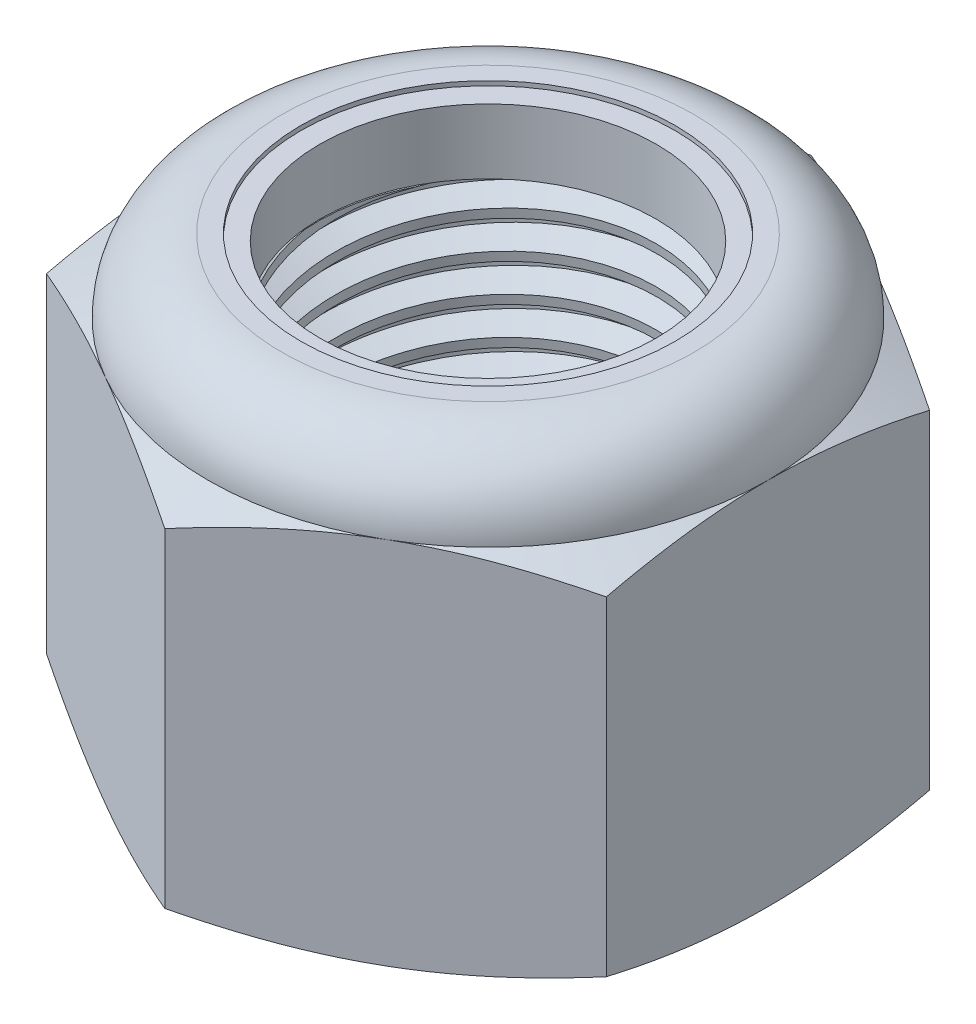
SolidWorks part; units mm, degrees
material "Plain Carbon Steel"
ref_plane "Front" through (0, 0, 0) normal (0, 0, 1) x (1, 0, 0)
ref_plane "Top" through (0, 0, 0) normal (0, 1, 0) x (1, 0, 0)
ref_plane "Right" through (0, 0, 0) normal (1, 0, 0) x (0, 0, -1)
sketch "Sketch1" plane through (0, 0, 0) normal (0, 1, 0) x (1, 0, 0)
  line L1 (0, 10.9985) -> (-9.525, 5.4993)
  line L2 (-9.525, 5.4993) -> (-9.525, -5.4993)
  line L3 (-9.525, -5.4993) -> (0, -10.9985)
  line L4 (0, -10.9985) -> (9.525, -5.4993)
  line L5 (9.525, -5.4993) -> (9.525, 5.4993)
  line L6 (9.525, 5.4993) -> (0, 10.9985)
  circle A0 centre (0, 0) radius 9.525 construction
  dimension "Hex Flats" = 19.05
extrude "Extrude1" add sketch "Sketch1" along normal blind 15.0812
sketch "Sketch2" plane through (0, 0, 0) normal (1, 0, 0) x (0, 0, -1)
  line L0 (-6.35, 0) -> (-6.35, 15.0812) construction
  line L1 (0, 0) -> (6.35, 0)
  line L2 (0, 0) -> (0, 15.0812)
  line L3 (0, 15.0812) -> (6.35, 15.0812)
  line L4 (6.35, 0) -> (6.35, 15.0812)
  line L5 (-5.4993, 15.0812) -> (5.4993, 15.0812) construction
  line L7 (0, -6.35) -> (0, 0) construction
  dimension "Thread Dia" = 12.7
revolve "Revolve1" add sketch "Sketch2" angle 360 about L7
sketch "Sketch3" plane through (0, 0, 0) normal (1, 0, 0) x (0, 0, -1)
  line L0 (6.35, 15.0813) -> (-6.35, 15.0813) construction
  line L1 (-6.35, 15.0813) -> (-6.35, 13.8113) construction
  line L2 (-6.35, 13.8113) -> (6.35, 15.0813) construction
  line L3 (6.35, 15.0813) -> (6.3658, 14.9233) construction
  line L4 (6.3658, 14.9233) -> (6.4764, 13.8176)
  line L5 (6.4764, 13.8176) -> (5.7529, 14.1441)
  line L6 (5.7529, 14.1441) -> (5.7213, 14.46)
  line L7 (5.7213, 14.46) -> (6.3658, 14.9233)
  line L8 (5.7371, 14.302) -> (6.4211, 14.3704) construction
  line L9 (6.35, 15.0813) -> (6.35, 14.3633) construction
  line L10 (6.35, 14.3633) -> (-6.35, 13.0933) construction
  line L11 (-6.35, 13.0933) -> (-6.35, 13.8113) construction
  line L12 (-0.1353, 15.0813) -> (0.1353, 12.3754) construction
  line L13 (-6.35, 0) -> (-6.35, 15.0812) construction
  line L14 (0, 15.0812) -> (6.35, 15.0812) construction
  line L15 (6.35, 0) -> (6.35, 15.0812) construction
  point P13 (0, 13.7283)
  dimension "D1" = 0.1588
  dimension "D2" = 0.3175
  dimension "Thread Pitch" = 1.27
  dimension "D4" = 60
  dimension "D5" = 1.27
revolve "Cut-Revolve1" cut sketch "Sketch3" angle 360 about L12
pattern_linear "LPattern1" count 12 spacing 1.27 along (0, -1, 0) count 2 spacing 1.27 along (0, 1, 0) of "Cut-Revolve1"
sketch "Sketch4" plane through (0, 0, 0) normal (1, 0, 0) x (0, 0, -1)
  line L0 (0, 15.0812) -> (6.35, 15.0812)
  line L1 (6.35, 15.0812) -> (5.7213, 14.7881)
  line L2 (5.7213, 14.7881) -> (5.7213, 0.2932)
  line L3 (5.7213, 0.2932) -> (6.35, 0)
  line L4 (6.35, 0) -> (0, 0)
  line L5 (0, 0) -> (0, 15.0812)
  line L6 (6.35, 0) -> (6.35, 15.0812) construction
  line L7 (0, 15.0812) -> (6.35, 15.0812) construction
  line L8 (0, 0) -> (6.35, 0) construction
  line L9 (0, 0) -> (0, 15.0812) construction
  line L10 (0, 15.0812) -> (0, 15.775) construction
  dimension "D1" = 25
revolve "Cut-Revolve2" cut sketch "Sketch4" angle 360 about L10
combine bodies "Combine1" operation type subtract main body 112 bodies to subtract 111
sketch "Sketch5" plane through (0, 0, 0) normal (1, 0, 0) x (0, 0, -1)
  line L0 (0, 0) -> (9.525, 0)
  line L1 (9.525, 0) -> (10.9985, 0.6871)
  line L2 (10.9985, 0.6871) -> (10.9985, 11.8806)
  line L3 (10.9985, 11.8806) -> (9.525, 12.5677)
  line L4 (7.0115, 15.0812) -> (7.0115, 16.3512)
  line L5 (7.0115, 16.3512) -> (12.2685, 16.3512)
  line L6 (12.2685, 16.3512) -> (12.2685, -1.27)
  line L7 (12.2685, -1.27) -> (0, -1.27)
  line L8 (0, -1.27) -> (0, 0)
  line L9 (9.525, 12.5677) -> (9.525, 0) construction
  line L10 (0, 0) -> (6.35, 0) construction
  line L13 (10.9985, 6.2839) -> (12.2685, 6.2839) construction
  line L14 (10.9985, 15.0812) -> (10.9985, 0) construction
  line L15 (0, 0) -> (0, 16.3512) construction
  line L20 (0, 16.3512) -> (7.0115, 16.3512) construction
  line L22 (0, 15.0812) -> (6.35, 15.0812) construction
  arc A0 (9.525, 12.5677) -> (7.0115, 15.0812) centre (7.0115, 12.5677) ccw
  dimension "D1" = 25
  dimension "D2" = 1.27
  dimension "D3" = 15.0812
  dimension "D4" = 2.5135
revolve "Cut-Revolve3" cut sketch "Sketch5" angle 360 about L15
sketch "Sketch6" plane through (0, 0, 0) normal (1, 0, 0) x (0, 0, -1)
  line L0 (0, 12.5677) -> (9.3726, 12.5677)
  line L1 (7.0115, 14.9289) -> (6.3664, 14.9289)
  line L2 (0, 16.3512) -> (0, 12.5677)
  line L3 (6.3664, 16.3512) -> (0, 16.3512)
  line L4 (0, 16.3512) -> (7.0115, 16.3512) construction
  line L5 (0, 0) -> (0, 16.3512) construction
  line L6 (0, 16.3512) -> (0, 44.323) construction
  line L7 (6.3664, 14.9289) -> (6.3664, 16.3512)
  line L8 (7.0115, 15.0812) -> (7.0115, 14.9289) construction
  line L9 (6.3664, 14.9289) -> (5.7213, 14.9289) construction
  line L10 (5.7213, 14.9289) -> (5.7213, 14.7881) construction
  arc A0 (9.3726, 12.5677) -> (7.0115, 14.9289) centre (7.0115, 12.5677) ccw
  arc A1 (9.525, 12.5677) -> (7.0115, 15.0812) centre (7.0115, 12.5677) ccw construction
  dimension "D1" = 0.1524
revolve "Cut-Revolve4" cut sketch "Sketch6" angle 360 about L6
sketch "Sketch7" plane through (0, 0, 0) normal (1, 0, 0) x (0, 0, -1)
  line L0 (5.7213, 12.6439) -> (9.2951, 12.6439)
  line L1 (7.0115, 14.8527) -> (5.7213, 14.8527)
  line L2 (5.7213, 14.8527) -> (5.7213, 12.6439)
  line L3 (5.7213, 12.6439) -> (0, 12.6439) construction
  line L4 (0, 12.6439) -> (0, 14.8527) construction
  line L5 (0, 14.8527) -> (5.7213, 14.8527) construction
  line L6 (5.7213, 12.6439) -> (5.7213, 12.5677) construction
  line L7 (0, 12.5677) -> (9.3726, 12.5677) construction
  line L8 (7.0115, 14.8527) -> (7.0115, 14.9289) construction
  arc A0 (9.2951, 12.6439) -> (7.0115, 14.8527) centre (7.0115, 12.5677) ccw
  arc A2 (9.3726, 12.5677) -> (7.0115, 14.9289) centre (7.0115, 12.5677) ccw construction
  dimension "D1" = 0.0762
revolve "Revolve2" add sketch "Sketch7" angle 360 about L4
equation "\"D1@Sketch3\"=\"Thread Pitch@Sketch3\"/8"
equation "\"D2@Sketch3\"=\"Thread Pitch@Sketch3\"/4"
equation "\"D5@Sketch3\"=\"Thread Pitch@Sketch3\""
equation "\"D4@LPattern1\"=\"Thread Pitch@Sketch3\""
equation "\"D3@LPattern1\"=\"Thread Pitch@Sketch3\""
equation "\"D1@LPattern1\"=\"Height@Extrude1\"/\"Thread Pitch@Sketch3\""
equation "\"D4@Sketch5\"=\"Height@Extrude1\"/6"
